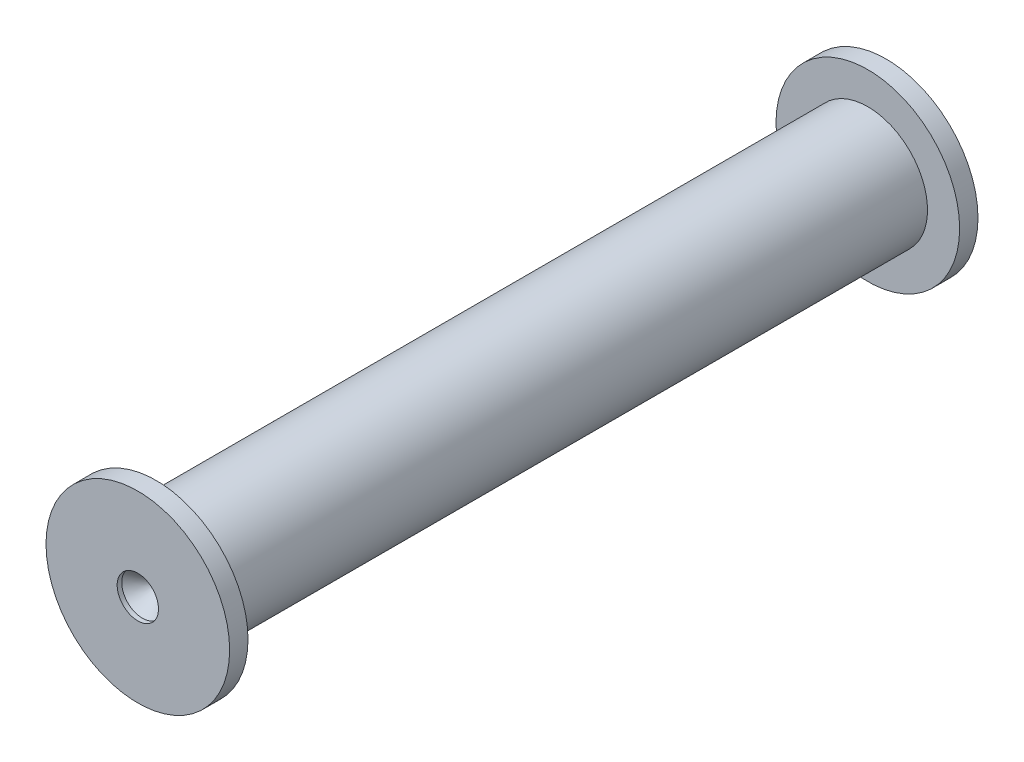
SolidWorks part; units mm, degrees
ref_plane "Ön Düzlem" through (0, 0, 0) normal (0, 0, 1) x (1, 0, 0)
ref_plane "Üst Düzlem" through (0, 0, 0) normal (0, 1, 0) x (1, 0, 0)
ref_plane "Sağ Düzlem" through (0, 0, 0) normal (1, 0, 0) x (0, 0, -1)
sketch "Çizim1" plane through (0, 0, 0) normal (0, 0, 1) x (1, 0, 0)
  circle A0 centre (3.3, -31.2819) radius 1.3
  dimension "D1" = 2.6
extrude "Yükseklik-Ekstrüzyon1" add sketch "Çizim1" against normal blind 15.4 and the other way blind 0.1
sketch "Çizim2" plane through (0, 0, 0.1) normal (0, 0, 1) x (1, 0, 0)
  circle A0 centre (3.3, -31.2819) radius 2
  dimension "D1" = 4
extrude "Yükseklik-Ekstrüzyon2" add sketch "Çizim2" along normal blind 0.4
sketch "Çizim3" plane through (0, 0, -15.4) normal (0, 0, -1) x (-1, 0, 0)
  circle A0 centre (-3.3, -31.2819) radius 2
  dimension "D1" = 4
extrude "Yükseklik-Ekstrüzyon3" add sketch "Çizim3" along normal blind 0.4
sketch "Çizim4" plane through (0, 0, -15.8) normal (0, 0, -1) x (-1, 0, 0)
  circle A0 centre (-3.3, -31.2819) radius 0.45
  dimension "D1" = 0.9
extrude "Kes-Ekstrüzyon1" cut sketch "Çizim4" against normal blind 0.5
chamfer "Pah1" distance 0.4 angle 45 1 edges at (2.85, -31.2819, -15.3)
sketch "Çizim5" plane through (0, 0, 0.5) normal (0, 0, 1) x (1, 0, 0)
  circle A0 centre (3.3, -31.2819) radius 0.45
  dimension "D1" = 0.9
extrude "Kes-Ekstrüzyon2" cut sketch "Çizim5" against normal blind 0.5
chamfer "Pah2" distance 0.4 angle 45 1 edges at (3.75, -31.2819, 0)
